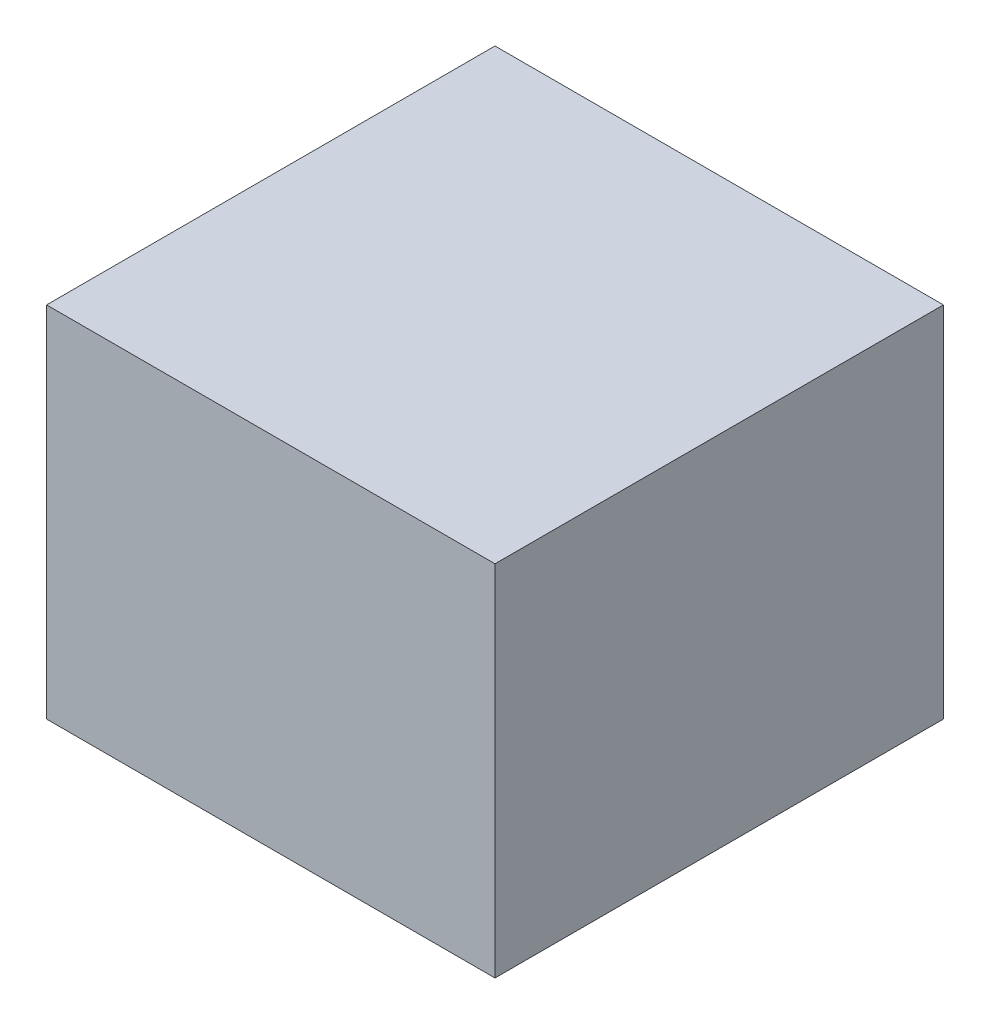
SolidWorks part; units mm, degrees
ref_plane "Front Plane" through (0, 0, 0) normal (0, 0, 1) x (1, 0, 0)
ref_plane "Top Plane" through (0, 0, 0) normal (0, 1, 0) x (1, 0, 0)
ref_plane "Right Plane" through (0, 0, 0) normal (1, 0, 0) x (0, 0, -1)
sketch "SK_P01_box" plane through (0, 0, 0) normal (0, 1, 0) x (1, 0, 0)
  line L0 (-25, -25) -> (25, -25)
  line L1 (25, -25) -> (25, 25)
  line L2 (25, 25) -> (-25, 25)
  line L3 (-25, 25) -> (-25, -25)
extrude "P01_box" add sketch "SK_P01_box" along normal blind 40
